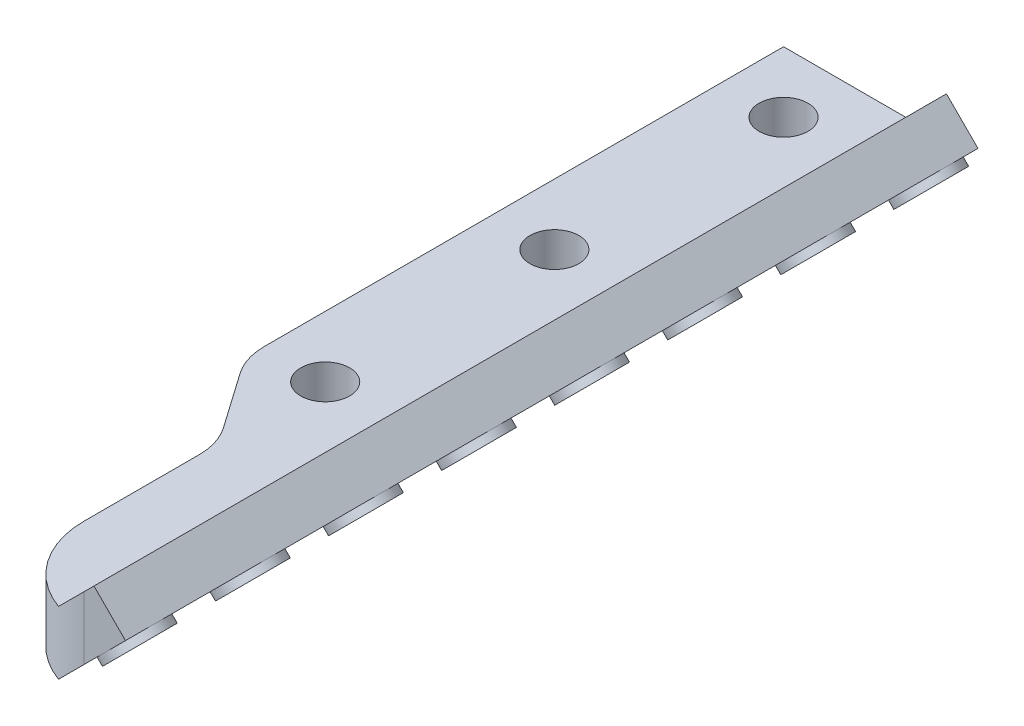
SolidWorks part; units mm, degrees
material "光敏树脂"
ref_plane "前视基准面" through (0, 0, 0) normal (0, 0, 1) x (1, 0, 0)
ref_plane "上视基准面" through (0, 0, 0) normal (0, 1, 0) x (1, 0, 0)
ref_plane "右视基准面" through (0, 0, 0) normal (1, 0, 0) x (0, 0, -1)
sketch "草图1" plane through (0, 0, 0) normal (0, 0, 1) x (1, 0, 0)
  line L0 (16.9, 0) -> (16.9, 3.4266) construction
  line L1 (16.9, 3.4266) -> (14.849, 5.4777) construction
  line L2 (14.849, 5.4777) -> (14.4954, 5.1241) construction
  line L3 (14.4954, 5.1241) -> (12.3741, 7.2454) construction
  line L4 (12.3741, 7.2454) -> (12.7277, 7.599)
  line L5 (12.7277, 7.599) -> (10.6633, 9.6633)
  line L6 (10.6633, 9.6633) -> (8, 7)
  line L7 (8, 7) -> (0, 7)
  line L8 (0, 7) -> (0, 0) construction
  line L9 (0, 0) -> (16.9, 0) construction
  line L10 (12.3741, 3.0028) -> (10.2528, 5.1241) construction
  line L11 (10.2528, 5.1241) -> (8, 2.8713)
  line L12 (8, 2.8713) -> (8, 1.5) construction
  line L13 (8, 1.5) -> (10.8713, 1.5) construction
  line L14 (10.8713, 1.5) -> (12.3741, 3.0028) construction
  line L15 (8, 2.8713) -> (0, 2.8713)
  line L16 (12.3741, 7.2454) -> (10.2528, 5.1241)
  line L17 (0, 7) -> (0, 2.8713)
  dimension "D1" = 3
  dimension "D2" = 45
  dimension "D3" = 16.9
  dimension "D4" = 3
  dimension "D5" = 1.5
  dimension "D6" = 8
  dimension "D7" = 7
  dimension "D8" = 3.4266
  dimension "D9" = 2.9006
  dimension "D10" = 0.5
extrude "凸台-拉伸1" add sketch "草图1" along normal blind 63.5
sketch "草图2" plane through (2.5643, -2.5643, 0) normal (0.7071, -0.7071, 0) x (0, 0, -1)
  line L0 (-63.5, 14.3731) -> (0, 14.3731) construction
  line L1 (0, 7.6872) -> (0, 14.3731) construction
  circle A0 centre (-2, 12.3731) radius 2
  dimension "D1" = 4
  dimension "D2" = 2
  dimension "D3" = 2
extrude "凸台-拉伸4" add sketch "草图2" along normal blind 0.5 contours A0
pattern_linear "阵列(线性)2" count 9 spacing 7.4 along (0, 0, 1) of "凸台-拉伸4"
sketch "草图4" plane through (0, 7, 0) normal (0, 1, 0) x (1, 0, 0)
  line L0 (0, -63.5) -> (0, 0) construction
  line L1 (8, 0) -> (0, 0) construction
  circle A0 centre (4, -4) radius 1.6
  dimension "D1" = 3.2
  dimension "D2" = 4
  dimension "D3" = 4
extrude "切除-拉伸1" cut sketch "草图4" against normal blind 10.5
pattern_linear "阵列(线性)3" count 3 spacing 15 along (0, 0, 1) of "切除-拉伸1"
sketch "草图5" plane through (0, 7, 0) normal (0, 1, 0) x (1, 0, 0)
  line L1 (4, -40.9738) -> (0.7234, -36.2943)
  line L2 (4, -34) -> (4, -40.9738) construction
  line L3 (0, -34) -> (-5.45, -34)
  line L4 (-5.45, -34) -> (-5.45, -68.0787)
  line L5 (-5.45, -68.0787) -> (16.2941, -68.0787)
  line L6 (16.2941, -68.0787) -> (16.2941, -55.8)
  line L7 (4, -40.9738) -> (4, -55.8)
  line L8 (4, -55.8) -> (16.2941, -55.8)
  line L9 (0, -63.5) -> (0, 0) construction
  arc A0 (0, -34) -> (0.7234, -36.2943) centre (4, -34) ccw
  circle A2 centre (4, -34) radius 1.6 construction
  dimension "D1" = 8
  dimension "D2" = 145
  dimension "D3" = 21.8
extrude "切除-拉伸2" cut sketch "草图5" against normal mid plane 40
fillet "圆角1" radius 6 1 edges at (4, 4.9357, 55.8)
fillet "圆角2" radius 4 1 edges at (4, 4.9357, 40.9738)
